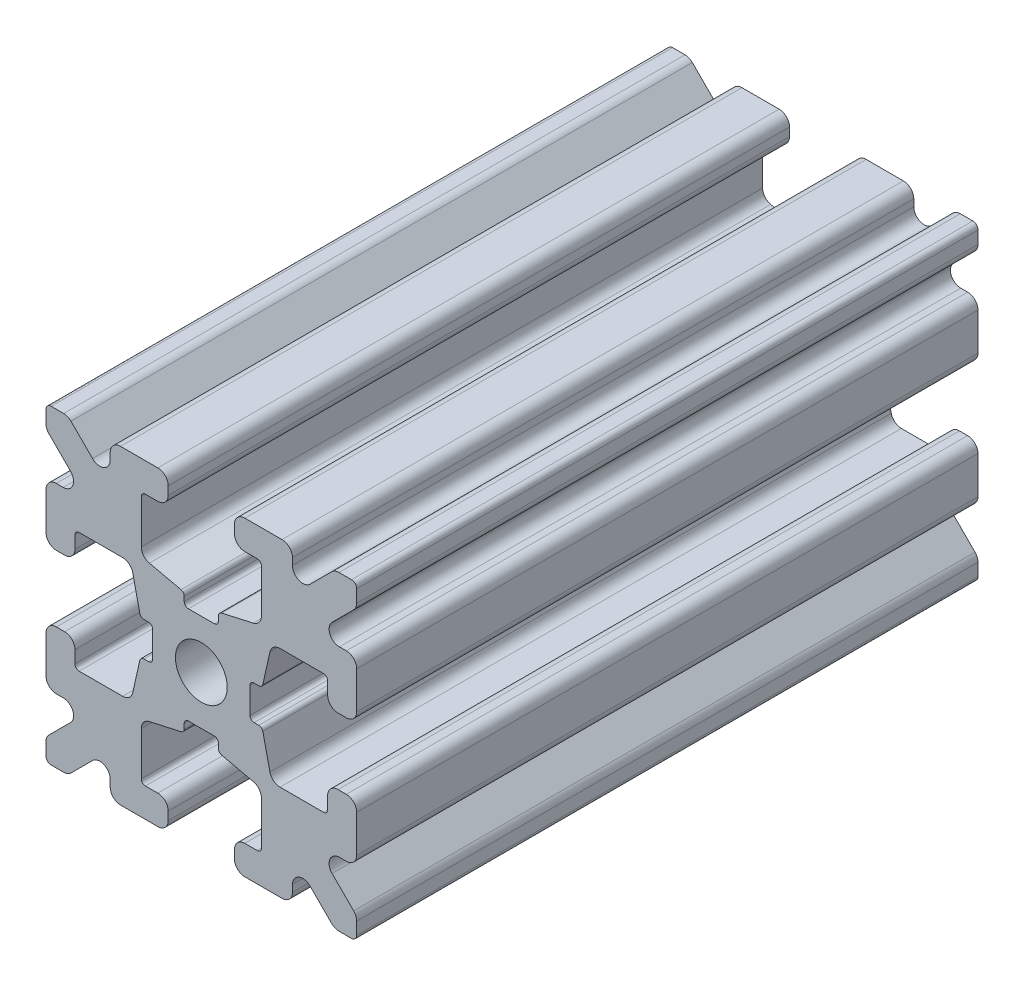
SolidWorks part; units mm, degrees
ref_plane "Front Plane" through (0, 0, 0) normal (0, 0, 1) x (1, 0, 0)
ref_plane "Top Plane" through (0, 0, 0) normal (0, 1, 0) x (1, 0, 0)
ref_plane "Right Plane" through (0, 0, 0) normal (1, 0, 0) x (0, 0, -1)
sketch "Sketch1" plane through (0, 0, 0) normal (0, 0, 1) x (1, 0, 0)
  line L1 (-7.5, -7.5) -> (7.5, -7.5)
  line L2 (-7.5, -7.5) -> (-7.5, 7.5)
  line L3 (-7.5, 7.5) -> (7.5, 7.5)
  line L4 (7.5, -7.5) -> (7.5, 7.5)
  line L5 (-7.5, -7.5) -> (7.5, 7.5) construction
  line L6 (-7.5, 7.5) -> (7.5, -7.5) construction
  circle A0 centre (0, 0) radius 1.25
  point P0 (0, 0)
  dimension "D2" = 2.5
  dimension "D1" = 15
extrude "Boss-Extrude1" add sketch "Sketch1" along normal mid plane 30
fillet "Fillet1" radius 0.25 4 edges at (7.5, -7.5, 0) (-7.5, -7.5, 0) (7.5, 7.5, 0) (-7.5, 7.5, 0)
sketch "Sketch2" plane through (0, 0, 15) normal (0, 0, 1) x (1, 0, 0)
  line L0 (-7.5, 7.25) -> (-7.5, -7.25) construction
  line L1 (-7.5, 1.6) -> (-6.1, 1.6)
  line L2 (-7.5, 1.6) -> (-7.5, -1.6)
  line L3 (-7.5, -1.6) -> (-6.1, -1.6)
  line L4 (-6.1, 1.6) -> (-6.1, 2.9)
  line L5 (0, 0) -> (-12.1036, 0) construction
  line L6 (-6.1, -2.9) -> (-3.4, -2.9)
  line L7 (0, 0) -> (-7.25, 7.25) construction
  line L8 (-6.1, 2.9) -> (-3.4, 2.9)
  line L9 (-3.4, -2.9) -> (-3.4, 2.9)
  line L10 (55, 0) -> (-55, 0) construction
  line L11 (-6.1, -2.9) -> (-6.1, -1.6)
  line L12 (2.9, 6.1) -> (1.6, 6.1)
  line L13 (2.9, 3.4) -> (-2.9, 3.4)
  line L14 (-2.9, 6.1) -> (-2.9, 3.4)
  line L15 (2.9, 6.1) -> (2.9, 3.4)
  line L16 (-1.6, 6.1) -> (-2.9, 6.1)
  line L17 (1.6, 7.5) -> (1.6, 6.1)
  line L18 (-1.6, 7.5) -> (1.6, 7.5)
  line L19 (-1.6, 7.5) -> (-1.6, 6.1)
  line L20 (-1.6, -7.5) -> (-1.6, -6.1)
  line L21 (-1.6, -7.5) -> (1.6, -7.5)
  line L22 (1.6, -7.5) -> (1.6, -6.1)
  line L23 (-1.6, -6.1) -> (-2.9, -6.1)
  line L24 (2.9, -6.1) -> (2.9, -3.4)
  line L25 (-2.9, -6.1) -> (-2.9, -3.4)
  line L26 (2.9, -3.4) -> (-2.9, -3.4)
  line L27 (2.9, -6.1) -> (1.6, -6.1)
  line L28 (6.1, -2.9) -> (6.1, -1.6)
  line L29 (3.4, -2.9) -> (3.4, 2.9)
  line L30 (6.1, 2.9) -> (3.4, 2.9)
  line L31 (6.1, -2.9) -> (3.4, -2.9)
  line L32 (6.1, 1.6) -> (6.1, 2.9)
  line L33 (7.5, -1.6) -> (6.1, -1.6)
  line L34 (7.5, 1.6) -> (7.5, -1.6)
  line L35 (7.5, 1.6) -> (6.1, 1.6)
  dimension "D1" = 3.2
  dimension "D2" = 5.8
  dimension "D3" = 1.4
  dimension "D4" = 2.7
extrude "Cut-Extrude1" cut sketch "Sketch2" against normal through all
sketch "Sketch4" plane through (0, 0, 15) normal (0, 0, 1) x (1, 0, 0)
  line L0 (-3.4, 2.9) -> (-2.75, 0)
  line L1 (55, 0) -> (-55, 0) construction
  line L2 (-2.75, 0) -> (-3.4, -2.9)
  line L3 (-3.4, -2.9) -> (-3.4, 2.9) construction
  line L4 (-3.4, 2.9) -> (-3.4, -2.9)
  line L5 (-2.9, 3.4) -> (0, 2.75)
  line L6 (0, 2.75) -> (2.9, 3.4)
  line L7 (2.9, 3.4) -> (-2.9, 3.4)
  line L8 (3.4, 2.9) -> (2.75, 0)
  line L9 (2.75, 0) -> (3.4, -2.9)
  line L10 (3.4, -2.9) -> (3.4, 2.9)
  line L11 (-2.9, -3.4) -> (0, -2.75)
  line L12 (0, -2.75) -> (2.9, -3.4)
  line L13 (2.9, -3.4) -> (-2.9, -3.4)
  circle A2 centre (0, 0) radius 2.75
  circle A3 centre (0, 0) radius 2.75 construction
  dimension "D1" = 1.5
extrude "Cut-Extrude3" cut sketch "Sketch4" against normal through all
fillet "Fillet3" radius 0.5 16 edges at (-6.1, -1.6, 0) (-7.5, -1.6, 0) (-6.1, 1.6, 0) (-7.5, 1.6, 0) (-1.6, -7.5, 0) (-1.6, -6.1, 0) (1.6, -7.5, 0) (1.6, -6.1, 0) (6.1, -1.6, 0) (7.5, -1.6, 0) (7.5, 1.6, 0) (6.1, 1.6, 0) (1.6, 7.5, 0) (1.6, 6.1, 0) (-1.6, 7.5, 0) (-1.6, 6.1, 0)
fillet "Fillet4" radius 0.5 8 edges at (-3.4, 2.9, 0) (-3.4, -2.9, 0) (2.9, -3.4, 0) (-2.9, -3.4, 0) (3.4, -2.9, 0) (3.4, 2.9, 0) (-2.9, 3.4, 0) (2.9, 3.4, 0)
fillet "Fillet5" radius 3 4 edges at (0, -2.75, 0) (2.75, 0, 0) (-2.75, 0, 0) (0, 2.75, 0)
fillet "Fillet6" radius 0.2 8 edges at (-2.9, -6.1, 0) (2.9, -6.1, 0) (6.1, -2.9, 0) (6.1, 2.9, 0) (2.9, 6.1, 0) (-2.9, 6.1, 0) (-6.1, -2.9, 0) (-6.1, 2.9, 0)
sketch "Sketch5" plane through (0, 0, 15) normal (0, 0, 1) x (1, 0, 0)
  line L0 (0, 0) -> (-7.25, 7.25) construction
  line L1 (-7.5, 6.4393) -> (-5.4607, 4.4)
  line L2 (-6.4393, 7.5) -> (-4.4, 5.4607)
  line L3 (-7.5, 4.4) -> (-5.4607, 4.4)
  line L4 (-3.8003, 2.9) -> (-5.9, 2.9) construction
  line L5 (0, 0) -> (-12.1819, 0) construction
  line L6 (-4.4, 7.5) -> (-4.4, 5.4607)
  line L7 (-2.9, 5.9) -> (-2.9, 3.8003) construction
  line L8 (-7.5, 6.4393) -> (-7.5, 4.4)
  line L9 (-7.5, 7.25) -> (-7.5, 2.1) construction
  line L10 (2.1, -7.5) -> (7.25, -7.5) construction
  line L11 (7.5, -7.25) -> (7.5, -2.1) construction
  line L12 (7.25, 7.5) -> (2.1, 7.5) construction
  line L13 (-2.1, 7.5) -> (-7.25, 7.5) construction
  line L14 (-4.4, 7.5) -> (-6.4393, 7.5)
  line L16 (55, 0) -> (-55, 0) construction
  line L17 (0, 0) -> (0, 10.993) construction
  line L18 (0, -54.6431) -> (0, 54.6431) construction
  line L20 (4.4, 7.5) -> (6.4393, 7.5)
  line L22 (7.5, 6.4393) -> (7.5, 4.4)
  line L23 (4.4, 7.5) -> (4.4, 5.4607)
  line L24 (7.5, 4.4) -> (5.4607, 4.4)
  line L25 (6.4393, 7.5) -> (4.4, 5.4607)
  line L26 (7.5, 6.4393) -> (5.4607, 4.4)
  line L27 (7.5, -6.4393) -> (5.4607, -4.4)
  line L28 (6.4393, -7.5) -> (4.4, -5.4607)
  line L29 (7.5, -4.4) -> (5.4607, -4.4)
  line L30 (4.4, -7.5) -> (4.4, -5.4607)
  line L31 (7.5, -6.4393) -> (7.5, -4.4)
  line L33 (4.4, -7.5) -> (6.4393, -7.5)
  line L36 (-4.4, -7.5) -> (-6.4393, -7.5)
  line L38 (-7.5, -6.4393) -> (-7.5, -4.4)
  line L39 (-4.4, -7.5) -> (-4.4, -5.4607)
  line L40 (-7.5, -4.4) -> (-5.4607, -4.4)
  line L41 (-6.4393, -7.5) -> (-4.4, -5.4607)
  line L42 (-7.5, -6.4393) -> (-5.4607, -4.4)
  dimension "D1" = 1.5
  dimension "D2" = 1.5
  dimension "D3" = 1.5
extrude "Cut-Extrude4" cut sketch "Sketch5" against normal through all
fillet "Fillet8" radius 0.5 24 edges at (-5.4607, 4.4, 0) (-7.5, 4.4, 0) (-5.4607, -4.4, 0) (-7.5, -4.4, 0) (-4.4, -7.5, 0) (-4.4, -5.4607, 0) (4.4, -7.5, 0) (4.4, -5.4607, 0) (5.4607, -4.4, 0) (7.5, -4.4, 0) (7.5, 4.4, 0) (5.4607, 4.4, 0) (4.4, 5.4607, 0) (4.4, 7.5, 0) (-4.4, 5.4607, 0) (-4.4, 7.5, 0) (-6.4393, 7.5, 0) (-7.5, 6.4393, 0) (6.4393, 7.5, 0) (7.5, 6.4393, 0) (6.4393, -7.5, 0) (7.5, -6.4393, 0) (-6.4393, -7.5, 0) (-7.5, -6.4393, 0)
sketch "Sketch6" plane through (0, 0, 15) normal (0, 0, 1) x (1, 0, 0)
  line L0 (0, 0) -> (0, 11.013) construction
  line L1 (0.6561, 2.8971) -> (2.1235, 2.8971) construction
  line L2 (0, -54.6431) -> (0, 54.6431) construction
  line L3 (0, 0) -> (7.25, 7.25) construction
  line L4 (7.5, 0.8255) -> (7.5, -0.8255)
  line L5 (2.3471, 0.8255) -> (7.5, 0.8255)
  line L6 (0, 0) -> (12.4016, 0) construction
  line L7 (0.8255, -7.5) -> (-0.8255, -7.5)
  line L8 (2.3471, -0.8255) -> (2.3471, 0.8255)
  line L9 (0.8255, -2.3471) -> (0.8255, -7.5)
  line L10 (7.5, -0.8255) -> (2.3471, -0.8255)
  line L11 (-7.5, -0.8255) -> (-2.3471, -0.8255)
  line L12 (-2.3471, -0.8255) -> (-2.3471, 0.8255)
  line L13 (-0.8255, -2.3471) -> (0.8255, -2.3471)
  line L14 (-0.8255, 7.5) -> (-0.8255, 2.3471)
  line L15 (-0.8255, 2.3471) -> (0.8255, 2.3471)
  line L16 (-0.8255, -7.5) -> (-0.8255, -2.3471)
  line L17 (0.8255, 2.3471) -> (0.8255, 7.5)
  line L18 (0.8255, 7.5) -> (-0.8255, 7.5)
  line L19 (3.9, 7.5) -> (2.1, 7.5) construction
  line L20 (-2.3471, 0.8255) -> (-7.5, 0.8255)
  line L21 (-7.5, 0.8255) -> (-7.5, -0.8255)
  point P5 (0, -2.5973)
  point P7 (0, 2.5973)
  dimension "D3" = 0.55
  dimension "D1" = 1.651
extrude "Cut-Extrude5" cut sketch "Sketch6" against normal through all
fillet "Fillet10" radius 0.2 16 edges at (-2.935, 0.8255, 0) (-2.935, -0.8255, 0) (2.935, -0.8255, 0) (2.935, 0.8255, 0) (0.8255, 2.935, 0) (-0.8255, 2.935, 0) (-2.3471, 0.8255, 0) (-2.3471, -0.8255, 0) (0.8255, 2.3471, 0) (-0.8255, 2.3471, 0) (2.3471, 0.8255, 0) (2.3471, -0.8255, 0) (0.8255, -2.935, 0) (0.8255, -2.3471, 0) (-0.8255, -2.3471, 0) (-0.8255, -2.935, 0)
